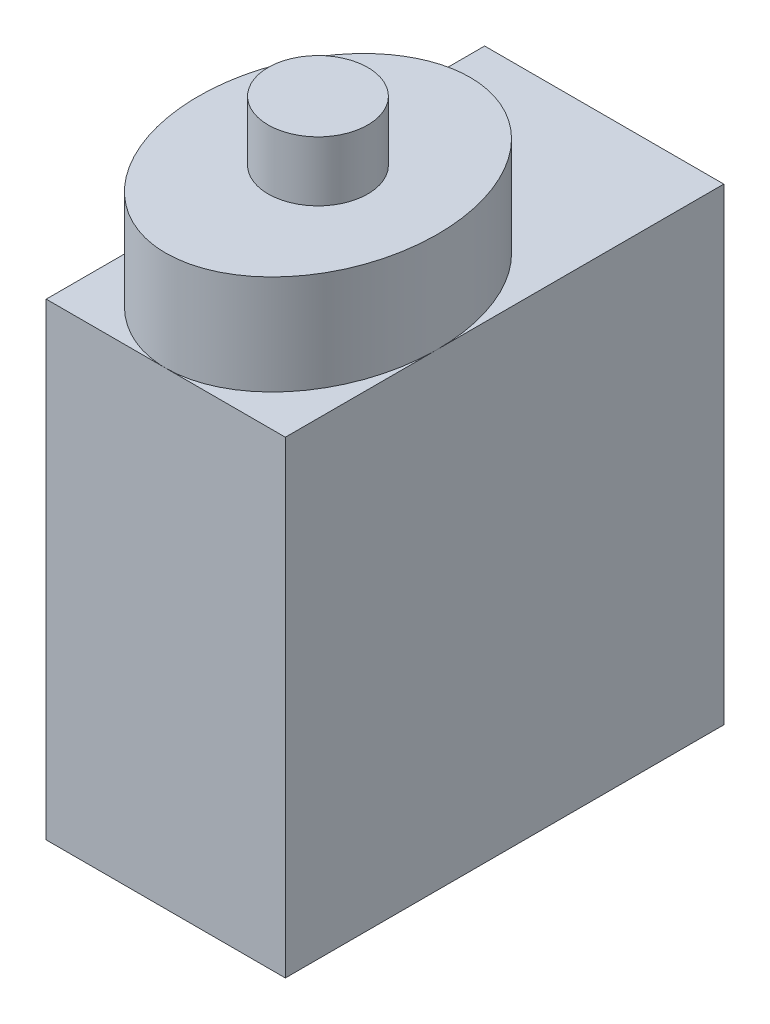
SolidWorks part; units mm, degrees
ref_plane "前视基准面" through (0, 0, 0) normal (0, 0, 1) x (1, 0, 0)
ref_plane "上视基准面" through (0, 0, 0) normal (0, 1, 0) x (1, 0, 0)
ref_plane "右视基准面" through (0, 0, 0) normal (1, 0, 0) x (0, 0, -1)
other "Configuration Table"
sketch "草图1" plane through (0, 0, 0) normal (0, 1, 0) x (1, 0, 0)
  line L1 (-6, -11) -> (6, -11)
  line L2 (-6, -11) -> (-6, 11)
  line L3 (-6, 11) -> (6, 11)
  line L4 (6, -11) -> (6, 11)
  line L5 (-6, -11) -> (6, 11) construction
  line L6 (-6, 11) -> (6, -11) construction
  point P0 (0, 0)
  dimension "D1" = 12
  dimension "D2" = 22
extrude "凸台-拉伸1" add sketch "草图1" along normal blind 16
sketch "草图2" plane through (0, 16, 0) normal (0, 1, 0) x (1, 0, 0)
  line L1 (-6, -16) -> (6, -16)
  line L2 (-6, -16) -> (-6, 16)
  line L3 (-6, 16) -> (6, 16)
  line L4 (6, -16) -> (6, 16)
  line L5 (-6, -16) -> (6, 16) construction
  line L6 (-6, 16) -> (6, -16) construction
  point P0 (0, 0)
  dimension "D2" = 32
  dimension "D1" = 12
extrude "凸台-拉伸2" add sketch "草图2" along normal blind 2.5
sketch "草图4" plane through (0, 18.5, 0) normal (0, 1, 0) x (1, 0, 0)
  line L1 (-6, -11) -> (6, -11)
  line L2 (-6, -11) -> (-6, 11)
  line L3 (-6, 11) -> (6, 11)
  line L4 (6, -11) -> (6, 11)
  line L5 (-6, -11) -> (6, 11) construction
  line L6 (-6, 11) -> (6, -11) construction
  point P0 (0, 0)
  dimension "D1" = 12
  dimension "D2" = 22
extrude "凸台-拉伸4" add sketch "草图4" along normal blind 5
sketch "草图5" plane through (0, 23.5, 0) normal (0, 1, 0) x (1, 0, 0)
  line L0 (-6, -11) -> (6, -11) construction
  ellipse E0 centre (0, -3.3628) end of major axis (0, -11) minor radius 6
extrude "凸台-拉伸5" add sketch "草图5" along normal blind 5
sketch "草图6" plane through (0, 28.5, 0) normal (0, 1, 0) x (1, 0, 0)
  circle A0 centre (0, -3.3628) radius 2.5
extrude "凸台-拉伸6" add sketch "草图6" along normal blind 3
sketch "草图7" plane through (-6, 0, 0) normal (-1, 0, 0) x (0, 0, 1)
  line L0 (-11, 18.5) -> (-16, 18.5)
  line L1 (-16, 18.5) -> (-11, 18.5) construction
  line L2 (-16, 18.5) -> (-16, 16)
  line L3 (-16, 18.5) -> (-16, 16) construction
  line L4 (-16, 16) -> (-11, 16)
  line L5 (-16, 16) -> (-11, 16) construction
  line L6 (-11, 16) -> (-11, 18.5)
  line L7 (11, 18.5) -> (11, 16)
  line L8 (11, 18.5) -> (16, 18.5) construction
  line L9 (11, 16) -> (16, 16)
  line L10 (16, 16) -> (16, 18.5)
  line L11 (16, 18.5) -> (11, 18.5)
extrude "切除-拉伸1" cut sketch "草图7" against normal through all
